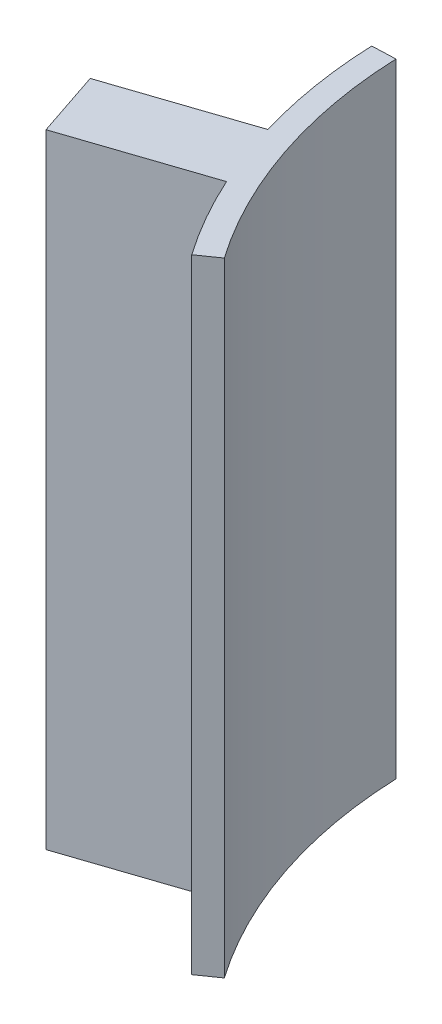
SolidWorks part; units mm, degrees
ref_plane "Front Plane" through (0, 0, 0) normal (0, 0, 1) x (1, 0, 0)
ref_plane "Top Plane" through (0, 0, 0) normal (0, 1, 0) x (1, 0, 0)
ref_plane "Right Plane" through (0, 0, 0) normal (1, 0, 0) x (0, 0, -1)
sketch "Sketch1" plane through (0, 0, 0) normal (0, 1, 0) x (1, 0, 0)
  line L0 (-61.9558, -2.3401) -> (-64.9537, -2.4533) construction
  line L1 (-61.9558, -2.3401) -> (-64.9537, -2.4533)
  line L2 (-53.3079, -37.1923) -> (-50.8475, -35.4757)
  line L4 (-76.5488, -32.6493) -> (-79.4094, -24.116)
  line L5 (-79.4094, -24.116) -> (-62.3429, -18.3947)
  line L6 (-76.5488, -32.6493) -> (-59.2024, -26.8342)
  arc A0 (-61.9558, -2.3401) -> (-50.8475, -35.4757) centre (0, 0) ccw
  arc A1 (-64.9537, -2.4533) -> (-62.3429, -18.3947) centre (0, 0) ccw
  arc A2 (-62.3429, -18.3947) -> (-64.9537, -2.4533) centre (0, 0) cw
  arc A3 (-62.3429, -18.3947) -> (-64.9537, -2.4533) centre (0, 0) cw
  arc A4 (-59.2024, -26.8342) -> (-53.3079, -37.1923) centre (0, 0) ccw
  arc A5 (-53.3079, -37.1923) -> (-59.2024, -26.8342) centre (0, 0) cw
  arc A6 (-53.3079, -37.1923) -> (-59.2024, -26.8342) centre (0, 0) cw
  point P13 (-77.9791, -28.3826)
  dimension "D1" = 4.5
  dimension "D2" = 62
  dimension "D3" = 65
  dimension "D4" = 18.2951
extrude "Boss-Extrude1" add sketch "Sketch1" along normal blind 80 contours L6 A4 L2 A0 L1 A1 L5 L4
sketch "Sketch3" plane through (2.1058, 0, 6.2814) normal (0.3179, 0, 0.9481) x (0.9481, 0, -0.3179)
  line L1 (-82.9566, 80) -> (-75.4566, 80) construction
  line L2 (-82.9566, 80) -> (-82.9566, 55) construction
  line L3 (-82.9566, 55) -> (-75.4566, 55) construction
  line L4 (-75.4566, 80) -> (-75.4566, 55) construction
  line L5 (-82.9566, 0) -> (-145.9366, 0) construction
  line L6 (-82.9566, 0) -> (-82.9566, 25) construction
  line L7 (-82.9566, 25) -> (-145.9366, 25) construction
  line L8 (-145.9366, 0) -> (-145.9366, 25) construction
  line L9 (-82.9566, 0) -> (-75.4566, 0) construction
  line L10 (-82.9566, 0) -> (-82.9566, 25) construction
  line L11 (-82.9566, 25) -> (-75.4566, 25) construction
  line L12 (-75.4566, 0) -> (-75.4566, 25) construction
  dimension "D1" = 7.5
  dimension "D2" = 25
  dimension "D3" = 25
